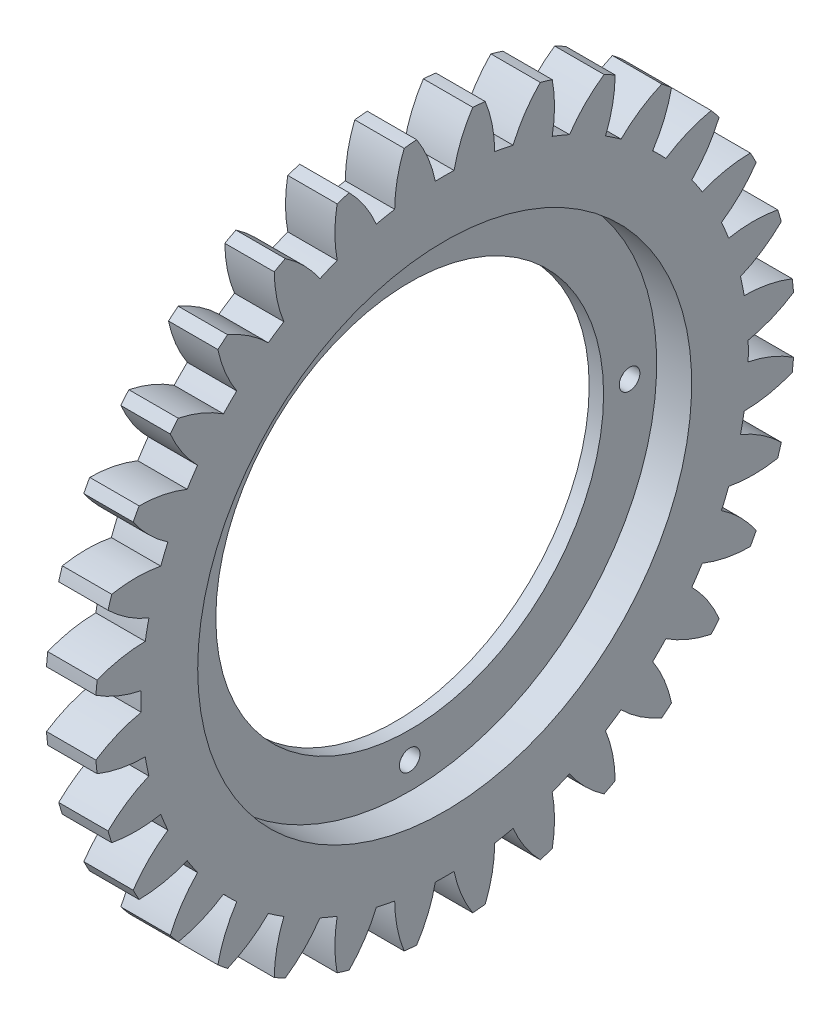
SolidWorks part; units mm, degrees
ref_plane "Plane1" through (0, 0, 0) normal (0, 0, 1) x (1, 0, 0)
ref_plane "Plane2" through (0, 0, 0) normal (0, 1, 0) x (1, 0, 0)
ref_plane "Plane3" through (0, 0, 0) normal (1, 0, 0) x (0, 0, -1)
sketch "HoldingSke" plane through (0, 0, 0) normal (0, 1, 0) x (1, 0, 0)
  line L0 (0, 0) -> (0.1696, -0.106)
  line L1 (-15, 0) -> (100, 0) construction
  line L2 (0, 0) -> (-2.1039, 2.3779)
  line L3 (0, 0) -> (-11.863, 4.5341)
  line L4 (0, 0) -> (7.3237, 4.5764)
  line L5 (0, 0) -> (-46.8476, -17.4728)
  line L6 (0, 0) -> (-9.9476, -6.7116)
  line L7 (-2.1039, 2.3779) -> (8.6586, 51.2059)
  line L8 (-76.2, 54.61) -> (-68.8, 54.61)
  line L9 (-71.009, 38.7566) -> (-53.1078, 45.2721)
  line L10 (-76.2, 71.12) -> (104.1128, 71.12)
  line L11 (0, 0) -> (-12, 0)
  line L12 (-76.2, 101.6) -> (-76.033, 101.6)
  line L13 (24.9733, 27.94) -> (52.9518, 28.4284)
  line L14 (24.9733, 27.94) -> (24.9743, 27.94)
  line L15 (24.9733, 27.94) -> (100.4006, 29.5858)
  line L16 (-63.627, -5) -> (-12.827, -5)
  circle A0 centre (0, 0) radius 60
  circle A1 centre (0, 0) radius 37.5
  circle A2 centre (0, 0) radius 37.5
  circle A3 centre (0, 0) radius 60
  dimension "MHD" = 75
  dimension "Hub_dia" = 75
  dimension "Bore" = 120
  dimension "MBD" = 120
  dimension "Num_teeth" = 32
  dimension "Pitch" = 0.2
  dimension "Overall_len" = 50
  dimension "Show_teeth" = 32
  dimension "Thickness" = 12
  dimension "OAL" = 50.0001
  dimension "T_dim" = 7.4
  dimension "Ap" = 20
  dimension "H" = 19.05
  dimension "Pitch_radius" = 180.3128
  dimension "Width" = 12
  dimension "Backlash" = 0.167
  dimension "Addendum_fac" = 1
  dimension "Dedendum_fac" = 1.25
  dimension "Clearance_fac" = 0.25
  dimension "Dedendum_add" = 0.001
  dimension "Module" = 5
sketch "BasProSke" plane through (0, 0, 0) normal (0, 1, 0) x (1, 0, 0)
  line L0 (-10, 0) -> (3.5, 0) construction
  line L1 (0, 0) -> (0, 85)
  line L2 (0, 0) -> (3.5, 0)
  line L3 (12, 60) -> (12, 85)
  line L4 (12, 85) -> (0, 85)
  line L5 (3.5, 0) -> (3.5, 60)
  line L6 (3.5, 60) -> (12, 60)
  line L7 (12, 0) -> (60, 0) construction
  point P7 (12, 0)
  point P10 (12, 0)
  point P11 (11.7781, 85)
  point P12 (0, 0)
  dimension "Thickness" = 12
  dimension "Diameter" = 170
  dimension "D1" = 8.5
  dimension "D2" = 60
  dimension "D4" = 12
revolve "Base-Revolve" add sketch "BasProSke" angle 360 about L0
sketch "TooCutSke" plane through (0, 0, 0) normal (1, 0, 0) x (0, 0, -1)
  line L1 (0, 0) -> (0, 107) construction
  line L2 (0, 0) -> (-4.2176, 79.8887) construction
  line L3 (0, 0) -> (-15.6666, 159.0653) construction
  line L4 (-4.2176, 79.8887) -> (-7.8333, 79.5326) construction
  arc A0 (2.2739, 73.7139) -> (-2.2739, 73.7139) centre (0, 0) ccw
  arc A1 (6.8274, 84.7508) -> (-6.8274, 84.7508) centre (0, 0) ccw
  circle A2 centre (0, 0) radius 80 construction
  circle A3 centre (0, 0) radius 75.1754 construction
  arc A4 (-2.2739, 73.7139) -> (-6.8274, 84.7508) centre (-33.6127, 67.2423) ccw
  arc A5 (6.8274, 84.7508) -> (2.2739, 73.7139) centre (33.6127, 67.2423) ccw
  dimension "Root_dia" = 147.498
  dimension "Overcut_dia" = 170.0508
  dimension "Pitch_dia" = 160
  dimension "Base_dia" = 150.3508
  dimension "Flank_rad" = 32
  dimension "Half_ang" = 5.625
  dimension "Half_CT" = 3.6332
extrude "ToothCut" cut sketch "TooCutSke" along normal through all
fillet "Breaks" [suppressed] radius 0.1
fillet "RootFillets" [suppressed] radius 1.251
pattern_circular "TeethCuts" count 32 every 11.25 about axis through (-10, 0, 0) along (1, 0, 0) of "ToothCut", "RootFillets", "Breaks"
sketch "HubNeaOneSke" plane through (0, 0, 0) normal (-1, 0, 0) x (0, 0, 1)
  circle A0 centre (0, 0) radius 37.5
  dimension "Diameter" = 75
extrude "HubNearOne" [suppressed] add sketch "HubNeaOneSke" along normal blind 38.0001
sketch "HubNeaBotSke" plane through (0, 0, 0) normal (-1, 0, 0) x (0, 0, 1)
  circle A0 centre (0, 0) radius 37.5
  dimension "Diameter" = 75
extrude "HubNearBoth" [suppressed] add sketch "HubNeaBotSke" along normal blind 19
ref_plane "FarPln" through (12, 0, 0) normal (1, 0, 0) x (0, 0, -1)
sketch "HubFarSke" plane through (12, 0, 0) normal (1, 0, 0) x (0, 0, -1)
  circle A0 centre (0, 0) radius 37.5
  dimension "Diameter" = 75
extrude "HubFar" [suppressed] add sketch "HubFarSke" along normal blind 19
sketch "BorSke" plane through (0, 0, 0) normal (1, 0, 0) x (0, 0, -1)
  circle A0 centre (0, 0) radius 47.1
  dimension "Diameter" = 94.2
extrude "Bore" cut sketch "BorSke" along normal mid plane 100.0001
sketch "KeySke" plane through (0, 0, 0) normal (1, 0, 0) x (0, 0, -1)
  line L0 (-16, 0) -> (-16, 67.4)
  line L1 (-16, 67.4) -> (16, 67.4)
  line L2 (16, 67.4) -> (16, 0)
  line L3 (0, 0) -> (0, 34) construction
  line L4 (-16, 0) -> (16, 0)
  dimension "Offset" = 67.4
  dimension "Width" = 32
extrude "Keyway" [suppressed] cut sketch "KeySke" along normal mid plane 100.0001
pattern_circular "Keyway2" [suppressed] count 2 every 90 about axis through (-10, 0, 0) along (1, 0, 0)
sketch "Sketch1" plane through (12, 0, 0) normal (1, 0, 0) x (0, 0, -1)
  circle A0 centre (0, 53.4) radius 2.5
  circle A1 centre (53.4, 0) radius 2.5
  circle A2 centre (0, -53.4) radius 2.5
  circle A3 centre (-53.4, 0) radius 2.5
  point P2 (0, 0)
  point P3 (0.0063, 53.9434)
  point P4 (0, 0)
  point P11 (0, 0)
  point P12 (0, 0)
  point P13 (0, 0)
  dimension "D1" = 5
  dimension "D3" = 53.4
  dimension "D4" = 73.7139
  dimension "D5" = 11.0127
  dimension "D6" = 6.8115
  dimension "D7" = 9.0854
  dimension "D2" = 4
extrude "Cut-Extrude1" cut sketch "Sketch1" against normal up to next
equation "' \"Module@HoldingSke\" = 6.35"
equation "' \"Num_teeth@HoldingSke\" = 12"
equation "' \"Ap@HoldingSke\" =  20"
equation "' \"Ap@HoldingSke\" = 20"
equation "' \"Width@HoldingSke\" = 0.5 * 25.4"
equation "' \"Hub_dia@HoldingSke\"= 1 * 25.4"
equation "' \"Hub_dia@HoldingSke\" = 1 * 25.4"
equation "' \"Overall_len@HoldingSke\" = 1.0 * 25.4"
equation "' \"Bore@HoldingSke\" = 0.75 * 25.4"
equation "' \"T_dim@HoldingSke\" = 0.1 * 25.4"
equation "' \"Width@KeySke\" = 0.25 * 25.4"
equation "' \"Show_teeth@HoldingSke\" = 13"
equation "' \"Backlash@HoldingSke\" = 0.009 * 25.4"
equation "' \"Addendum_fac@HoldingSke\" = 1.0"
equation "' \"Dedendum_fac@HoldingSke\" = 1.25"
equation "' \"Dedendum_add@HoldingSke\" = 0.00005 * 25.4"
equation "' \"Clearance_fac@HoldingSke\" = 0.25"
equation "\"Pitch@HoldingSke\" = 1 / \"Module@HoldingSke\""
equation "\"Overcut_dia@TooCutSke\" = (\"Num_teeth@HoldingSke\" + 2 * \"Addendum_fac@HoldingSke\") / \"Pitch@HoldingSke\" + 0.002 * 25.4"
equation "\"Pitch_dia@TooCutSke\" = \"Num_teeth@HoldingSke\" / \"Pitch@HoldingSke\""
equation "\"Base_dia@TooCutSke\" = \"Num_teeth@HoldingSke\" / \"Pitch@HoldingSke\" * cos((\"Ap@HoldingSke\"  * 3.14159265 / 180))"
equation "\"Root_dia@TooCutSke\" = (\"Num_teeth@HoldingSke\" + 2) / \"Pitch@HoldingSke\" - 2 * (\"Addendum_fac@HoldingSke\" + \"Dedendum_fac@HoldingSke\") / \"Pitch@HoldingSke\" - \"Dedendum_add@HoldingSke\" * 2"
equation "\"Half_ang@TooCutSke\" = 180 / \"Num_teeth@HoldingSke\""
equation "\"Half_CT@TooCutSke\" = \"Num_teeth@HoldingSke\" / \"Pitch@HoldingSke\" * sin((3.14159265 / 2 / \"Num_teeth@HoldingSke\")) / 2 - 7 * \"Backlash@HoldingSke\" / 4"
equation "\"Flank_rad@TooCutSke\" = \"Num_teeth@HoldingSke\" / \"Pitch@HoldingSke\" / 5"
equation "\"Radius@RootFillets\" = \"Clearance_fac@HoldingSke\" / \"Pitch@HoldingSke\" + \"Dedendum_add@HoldingSke\""
equation "\"Break_rad@Breaks\" = 0.02 / \"Pitch@HoldingSke\""
equation "\"Thickness@HoldingSke\" = \"Width@HoldingSke\""
equation "\"OAL@HoldingSke\" = \"Thickness@HoldingSke\""
equation "\"MHD@HoldingSke\" = (\"Num_teeth@HoldingSke\" + 2) / \"Pitch@HoldingSke\" - 2 * (\"Addendum_fac@HoldingSke\" + \"Dedendum_fac@HoldingSke\")  / \"Pitch@HoldingSke\" - \"Dedendum_add@HoldingSke\" * 2"
equation "\"MBD@HoldingSke\" = (\"Num_teeth@HoldingSke\" + 2) / \"Pitch@HoldingSke\" - 2 * (\"Addendum_fac@HoldingSke\" + \"Dedendum_fac@HoldingSke\")  / \"Pitch@HoldingSke\" - \"Dedendum_add@HoldingSke\" * 2 - 0.002 * 25.4"
equation "\"MHD@HoldingSke\" = ((sgn( \"MHD@HoldingSke\" - \"Hub_dia@HoldingSke\" )-1)*( \"MHD@HoldingSke\" - \"Hub_dia@HoldingSke\" ))/-2+ \"Hub_dia@HoldingSke\""
equation "\"MBD@HoldingSke\" = ((sgn( \"MBD@HoldingSke\" - \"Bore@HoldingSke\" )-1)*( \"MBD@HoldingSke\" - \"Bore@HoldingSke\" ))/-2+ \"Bore@HoldingSke\""
equation "\"OAL@HoldingSke\" = ((sgn( \"OAL@HoldingSke\" - \"Overall_len@HoldingSke\" )+1)*( \"OAL@HoldingSke\" - \"Overall_len@HoldingSke\" ))/2 + \"Overall_len@HoldingSke\" + 0.000002 * 25.4"
equation "\"Num_teeth@TeethCuts\" = int( \"Show_teeth@HoldingSke\" ) + 1"
equation "\"Num_teeth@TeethCuts\" = ((sgn( \"Num_teeth@TeethCuts\" - \"Num_teeth@HoldingSke\" )-1)*( \"Num_teeth@TeethCuts\" - \"Num_teeth@HoldingSke\" ))/-2+ \"Num_teeth@HoldingSke\""
equation "\"Num_teeth@TeethCuts\" = ((sgn( \"Num_teeth@TeethCuts\" - 2.0)+1)*( \"Num_teeth@TeethCuts\" - 2.0))/2 +2.0"
equation "\"Angle@TeethCuts\" = 360.0 / \"Num_teeth@HoldingSke\""
equation "\"Diameter@BasProSke\" = (\"Num_teeth@HoldingSke\" + 2 * \"Addendum_fac@HoldingSke\") / \"Pitch@HoldingSke\""
equation "\"Thickness@BasProSke\"  = \"Thickness@HoldingSke\""
equation "' \"Fillet_rad@BasProSke\" =  \"Thickness@HoldingSke\" * 0.05"
equation "' \"Fillet_rad@BasProSke\" = \"Thickness@HoldingSke\" * 0.05"
equation "\"MHD@HoldingSke\" = ((sgn( \"MHD@HoldingSke\" - \"Root_dia@TooCutSke\" )-1)*( \"MHD@HoldingSke\" - \"Root_dia@TooCutSke\" ))/-2+ \"Root_dia@TooCutSke\""
equation "\"Diameter@HubNeaOneSke\" = \"MHD@HoldingSke\""
equation "\"Length@HubNearOne\" = \"OAL@HoldingSke\" - \"Thickness@BasProSke\""
equation "\"Diameter@HubNeaBotSke\" = \"MHD@HoldingSke\""
equation "\"Length@HubNearBoth\" = ( \"OAL@HoldingSke\" - \"Thickness@BasProSke\" ) / 2.0"
equation "\"Thickness@FarPln\" = \"Thickness@BasProSke\""
equation "\"Diameter@HubFarSke\" = \"MHD@HoldingSke\""
equation "\"Length@HubFar\" = ( \"OAL@HoldingSke\" - \"Thickness@BasProSke\" ) / 2.0"
equation "\"Diameter@BorSke\"=94.2"
equation "\"D1@Bore\" = \"OAL@HoldingSke\" * 2.0"
equation "\"D1@Keyway\" = \"OAL@HoldingSke\" * 2.0"
equation "\"Offset@KeySke\" = \"T_dim@HoldingSke\" + \"MBD@HoldingSke\" / 2.0"
